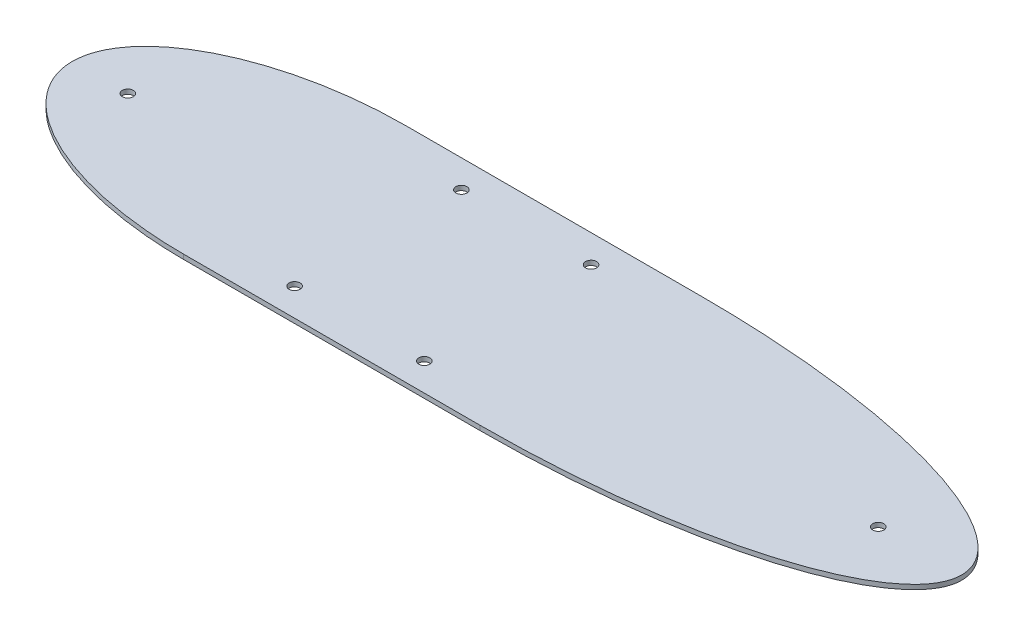
SolidWorks part; units mm, degrees
ref_plane "Front Plane" through (0, 0, 0) normal (0, 0, 1) x (1, 0, 0)
ref_plane "Top Plane" through (0, 0, 0) normal (0, 1, 0) x (1, 0, 0)
ref_plane "Right Plane" through (0, 0, 0) normal (1, 0, 0) x (0, 0, -1)
sketch "Sketch1" plane through (0, 0, 0) normal (0, 1, 0) x (1, 0, 0)
  line L1 (76.2, 38.1) -> (177.8, 38.1)
  line L3 (76.2, -38.1) -> (177.8, -38.1)
  ellipse E0 centre (76.2, 0) end of major axis (0, 0) minor radius 38.1 (76.2, 38.1) -> (76.2, -38.1) ccw
  ellipse E1 centre (177.8, 0) end of major axis (304.8, 0) minor radius 38.1 (177.8, -38.1) -> (177.8, 38.1) ccw
  point P0 (0, 0)
  dimension "D1" = 101.6
  dimension "D2" = 76.2
  dimension "D3" = 127
  dimension "D4" = 76.2
sketch "Sketch11" plane through (0, 0, 0) normal (0, 1, 0) x (1, 0, 0)
  line L4 (177.8, 38.1) -> (76.2, 38.1)
  line L5 (76.2, -38.1) -> (177.8, -38.1)
  line L6 (177.8, 38.1) -> (76.2, 38.1)
  line L7 (76.2, -38.1) -> (177.8, -38.1)
  spline S0 degree 3 poles (177.8, -38.1) (431.8, -38.1) (431.8, 38.1) (177.8, 38.1) knots 0 0 0 0 1 1 1 1 weights 1 0.333333 0.333333 1
  spline S1 degree 3 poles (76.2, 38.1) (-76.2, 38.1) (-76.2, -38.1) (76.2, -38.1) knots 0 0 0 0 1 1 1 1 weights 1 0.333333 0.333333 1
  spline S2 degree 3 poles (177.8, -38.1) (431.8, -38.1) (431.8, 38.1) (177.8, 38.1) knots 0 0 0 0 1 1 1 1 weights 1 0.333333 0.333333 1
  spline S3 degree 3 poles (76.2, 38.1) (-76.2, 38.1) (-76.2, -38.1) (76.2, -38.1) knots 0 0 0 0 1 1 1 1 weights 1 0.333333 0.333333 1
  dimension "D1" = 0
extrude "Boss-Extrude1" add sketch "Sketch11" along normal blind 1.5875
hole_wizard "#6 Clearance Hole1" positions "Sketch12" profile "Sketch13" hole size "#6" standard "ANSI Inch" end condition through all
sketch "Sketch12" plane through (0, 0, 0) normal (0, -1, 0) x (-1, 0, 0)
  point P0 (-104.775, -28.575)
  point P2 (-149.225, -28.575)
  point P4 (-149.225, 28.575)
  point P6 (-104.775, 28.575)
  dimension "D1" = 44.45
  dimension "D2" = 57.15
  dimension "D3" = 28.575
  dimension "D4" = 28.575
sketch "Sketch13" plane through (104.775, 0, 28.575) normal (1, 0, 0) x (0, 0, -1)
  line L0 (0, 0) -> (0, 1.5875)
  line L1 (0, 1.5875) -> (1.8986, 1.5875)
  line L2 (1.8986, 1.5875) -> (1.8986, 0)
  line L5 (1.8986, 0) -> (0, 0)
  line L11 (0, -6.35) -> (0, 107.95) construction
  dimension "Thru Hole Dia." = 3.7973
  dimension "Thru Hole Depth" = 1.5875
hole_wizard "#6 Clearance Hole2" positions "Sketch14" profile "Sketch15" hole size "#6" standard "ANSI Inch"
sketch "Sketch14" plane through (0, 0, 0) normal (0, -1, 0) x (-1, 0, 0)
  point P0 (-19.05, 0)
  point P4 (0, 0)
  dimension "D1" = 19.05
sketch "Sketch15" plane through (19.05, 0, 0) normal (1, 0, 0) x (0, 0, -1)
  line L0 (0, 0) -> (0, 26.5408)
  line L1 (0, 26.5408) -> (1.8986, 25.4)
  line L2 (1.8986, 25.4) -> (1.8986, 0)
  line L5 (1.8986, 0) -> (0, 0)
  line L10 (0, 26.5408) -> (-1.8987, 25.4) construction
  line L11 (0, -6.35) -> (0, 107.95) construction
  dimension "Hole Dia." = 3.7973
  dimension "Hole Depth" = 25.4
  dimension "Drill Angle" = 118
hole_wizard "#6 Clearance Hole3" positions "Sketch16" profile "Sketch17" hole size "#6" standard "ANSI Inch"
sketch "Sketch16" plane through (0, 0, 0) normal (0, -1, 0) x (-1, 0, 0)
  point P0 (-276.225, 0)
  point P4 (0, 0)
  dimension "D1" = 28.575
sketch "Sketch17" plane through (276.225, 0, 0) normal (1, 0, 0) x (0, 0, -1)
  line L0 (0, 0) -> (0, 26.5408)
  line L1 (0, 26.5408) -> (1.8986, 25.4)
  line L2 (1.8986, 25.4) -> (1.8986, 0)
  line L5 (1.8986, 0) -> (0, 0)
  line L10 (0, 26.5408) -> (-1.8987, 25.4) construction
  line L11 (0, -6.35) -> (0, 107.95) construction
  dimension "Hole Dia." = 3.7973
  dimension "Hole Depth" = 25.4
  dimension "Drill Angle" = 118
